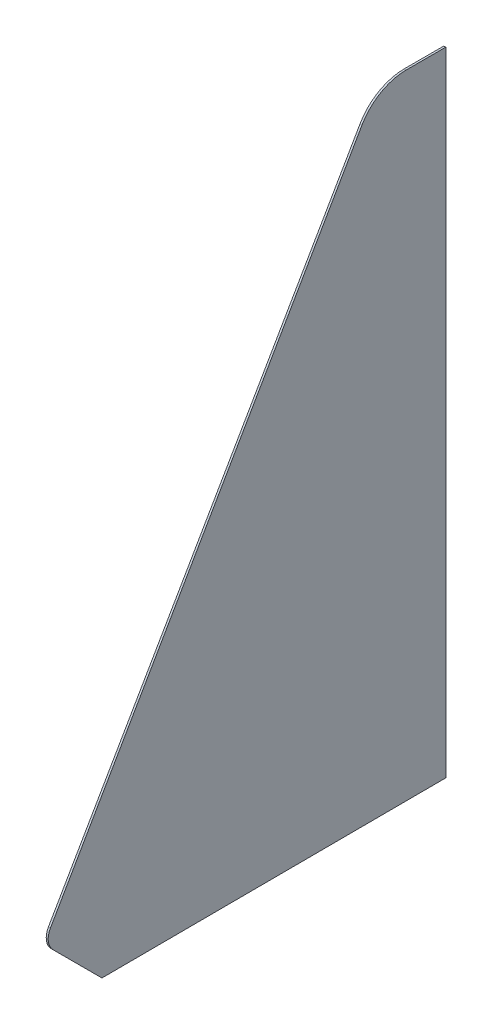
SolidWorks part; units mm, degrees
ref_plane "Front Plane" through (0, 0, 0) normal (0, 0, 1) x (1, 0, 0)
ref_plane "Top Plane" through (0, 0, 0) normal (0, 1, 0) x (1, 0, 0)
ref_plane "Right Plane" through (0, 0, 0) normal (1, 0, 0) x (0, 0, -1)
sketch "Sketch1" plane through (0, 0, 0) normal (1, 0, 0) x (0, 0, -1)
  line L0 (0, 642) -> (-40, 642)
  line L1 (-85.0333, 616) -> (-401.0333, 68.6719)
  line L2 (-348.7664, -1.4142) -> (-398.3317, 48.1511)
  line L3 (0, 642) -> (0, 0)
  line L4 (0, 0) -> (-348.7664, -1.4142)
  arc A0 (-398.3317, 48.1511) -> (-401.0333, 68.6719) centre (-386.3109, 60.1719) cw
  arc A1 (-40, 642) -> (-85.0333, 616) centre (-40, 590) ccw
surface "Surface-Plane1" sketch "Sketch1"
thicken "Thicken1" surfaces to thicken 101 thickness 2 parameters "D1"=2
